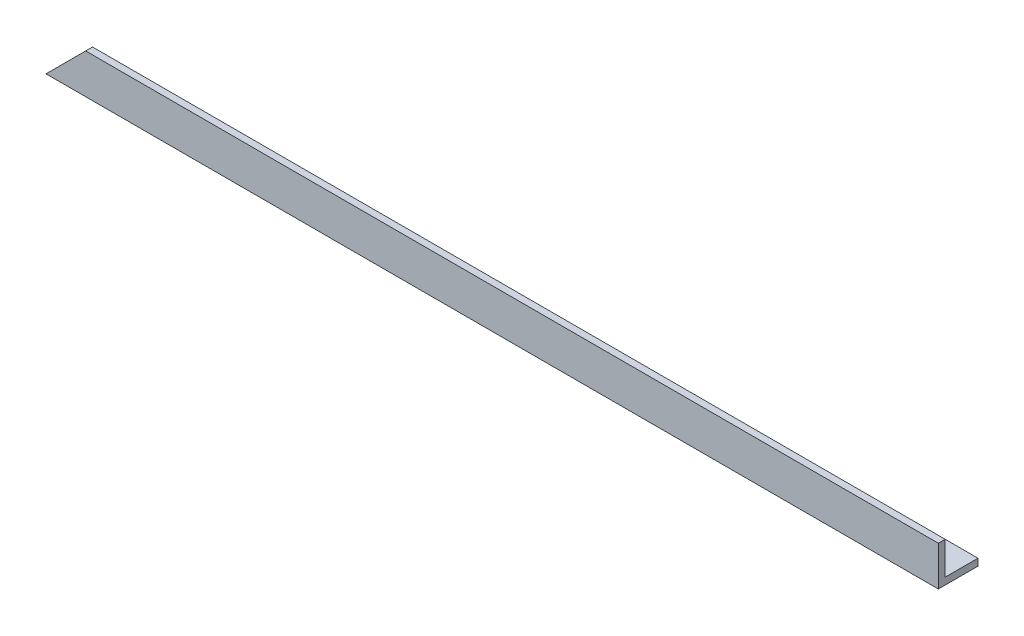
SolidWorks part; units mm, degrees
ref_plane "Front Plane" through (0, 0, 0) normal (0, 0, 1) x (1, 0, 0)
ref_plane "Top Plane" through (0, 0, 0) normal (0, 1, 0) x (1, 0, 0)
ref_plane "Right Plane" through (0, 0, 0) normal (1, 0, 0) x (0, 0, -1)
sketch "Sketch1" plane through (0, 0, 0) normal (1, 0, 0) x (0, 0, -1)
  line L0 (0, 0) -> (20, 0)
  line L1 (20, 0) -> (20, 3.4612)
  line L2 (20, 3.4612) -> (3.4612, 3.4612)
  line L3 (3.4612, 3.4612) -> (3.4612, 20)
  line L4 (3.4612, 20) -> (0, 20)
  line L5 (0, 20) -> (0, 0)
  dimension "D1" = 3.4612
  dimension "D2" = 20
extrude "Boss-Extrude1" add sketch "Sketch1" along normal blind 450
sketch "Sketch2" plane through (0, 0, 0) normal (0, 0, -1) x (1, 0, 0)
  line L11 (0, -20) -> (0, 0)
  line L15 (0, 0) -> (20, -20)
  line L16 (450, -20) -> (0, -20) construction
  line L17 (20, -20) -> (0, -20)
extrude "Cut-Extrude1" cut sketch "Sketch2" along normal through all
